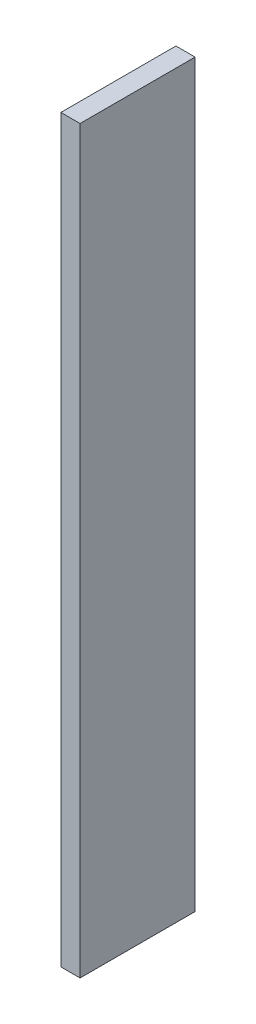
SolidWorks part; units mm, degrees
ref_plane "Спереди" through (0, 0, 0) normal (0, 0, 1) x (1, 0, 0)
ref_plane "Сверху" through (0, 0, 0) normal (0, 1, 0) x (1, 0, 0)
ref_plane "Справа" through (0, 0, 0) normal (1, 0, 0) x (0, 0, -1)
sketch "Эскиз1" plane through (0, 0, 0) normal (0, 1, 0) x (1, 0, 0)
  line L1 (0, 0) -> (5, 0)
  line L2 (0, 0) -> (0, -30)
  line L3 (0, -30) -> (5, -30)
  line L4 (5, 0) -> (5, -30)
  dimension "D1" = 5
  dimension "D2" = 30
extrude "Бобышка-Вытянуть1" add sketch "Эскиз1" along normal blind 193
